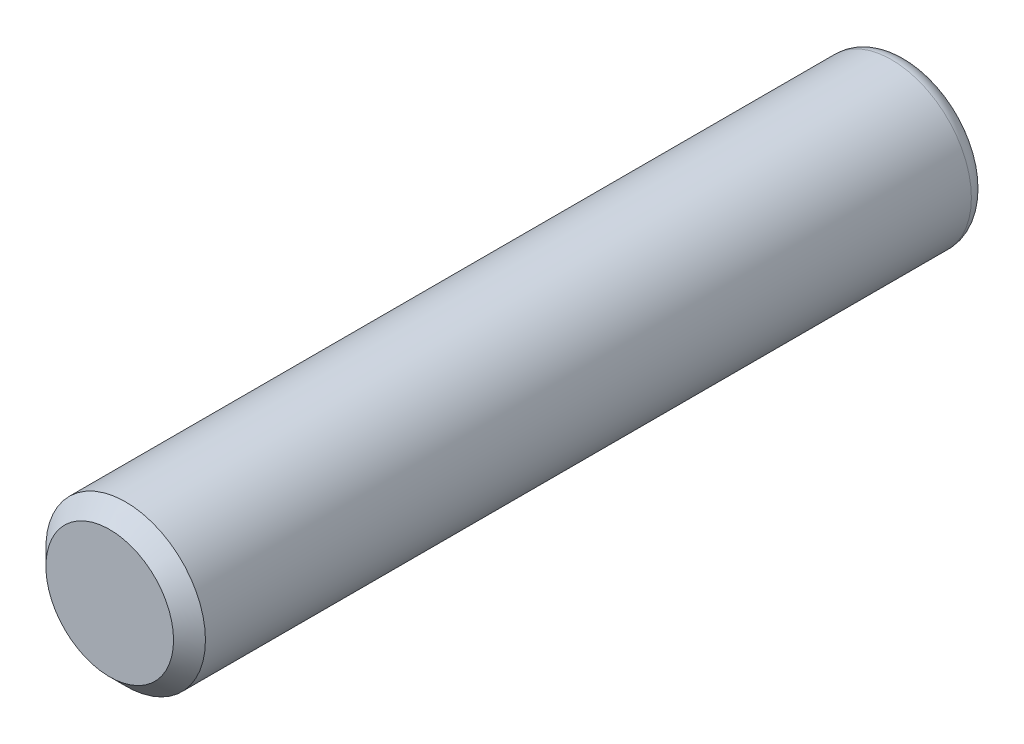
SolidWorks part; units mm, degrees
ref_plane "Front Plane" through (0, 0, 0) normal (0, 0, 1) x (1, 0, 0)
ref_plane "Top Plane" through (0, 0, 0) normal (0, 1, 0) x (1, 0, 0)
ref_plane "Right Plane" through (0, 0, 0) normal (1, 0, 0) x (0, 0, -1)
sketch "Sketch1" plane through (0, 0, 0) normal (1, 0, 0) x (0, 0, -1)
  line L0 (-7.9375, 0) -> (-7.9375, 1.27)
  line L1 (-7.9375, 1.27) -> (-7.62, 1.5875)
  line L2 (-7.62, 1.5875) -> (7.62, 1.5875)
  line L4 (7.9375, 1.27) -> (7.9375, 0)
  line L5 (7.9375, 0) -> (-7.9375, 0) construction
  line L6 (-7.9375, 0) -> (7.9375, 0)
  arc A0 (7.9375, 1.27) -> (7.62, 1.5875) centre (7.62, 1.27) ccw
  dimension "D3" = 0.3175
  dimension "D1" = 135
  dimension "Diameter" = 3.175
  dimension "D2" = 0.3175
  dimension "Length" = 15.875
sketch "Sketch2" plane through (0, 0, 0) normal (1, 0, 0) x (0, 0, -1)
  line L0 (7.9375, 1.27) -> (7.9375, 0) construction
  line L1 (-7.9375, 0) -> (7.9375, 0) construction
  line L2 (-7.9375, 1.27) -> (-7.62, 1.5875) construction
  line L3 (-7.62, 1.5875) -> (7.62, 1.5875) construction
  line L4 (-7.9375, 0) -> (-7.9375, 1.27) construction
  line L5 (7.9375, 1.27) -> (7.9375, 0)
  line L6 (-7.9375, 0) -> (7.9375, 0)
  line L7 (-7.9375, 1.27) -> (-7.62, 1.5875)
  line L8 (-7.62, 1.5875) -> (7.62, 1.5875)
  line L9 (-7.9375, 0) -> (-7.9375, 1.27)
  arc A0 (7.9375, 1.27) -> (7.62, 1.5875) centre (7.62, 1.27) ccw construction
  arc A1 (7.9375, 1.27) -> (7.62, 1.5875) centre (7.62, 1.27) ccw
revolve "Revolve1" add sketch "Sketch2" angle 360 about L6
sketch "Sketch3" plane through (0, 0, 0) normal (0, 0, 1) x (1, 0, 0)
  circle A0 centre (0, 0) radius 1.5875 construction
  circle A1 centre (0, 0) radius 1.5875
  dimension "D1" = 3.175
equation "\"D2@Sketch1\"=\"Diameter@Sketch1\"*.1"
equation "\"D3@Sketch1\"=\"Diameter@Sketch1\"*.1"
